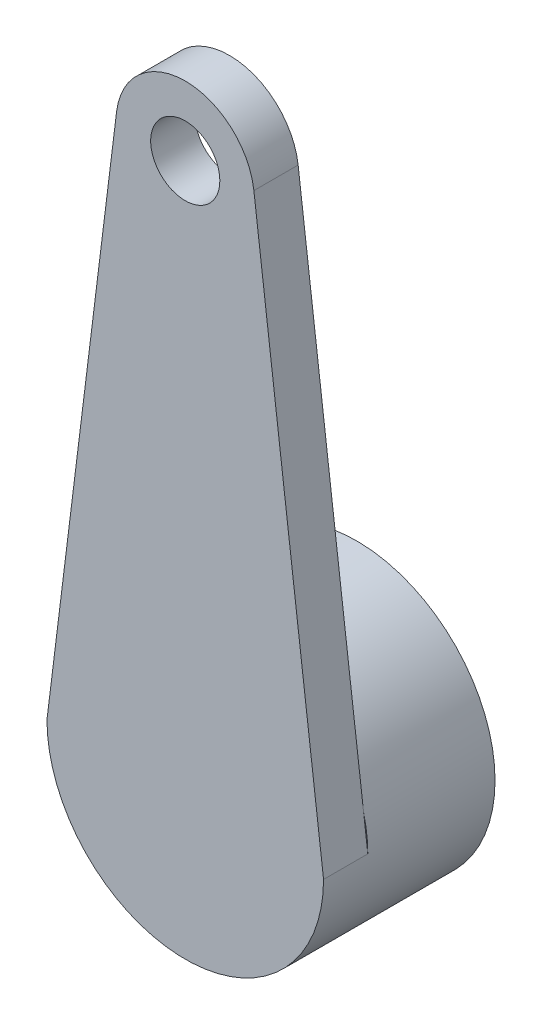
SolidWorks part; units mm, degrees
ref_plane "Front Plane" through (0, 0, 0) normal (0, 0, 1) x (1, 0, 0)
ref_plane "Top Plane" through (0, 0, 0) normal (0, 1, 0) x (1, 0, 0)
ref_plane "Right Plane" through (0, 0, 0) normal (1, 0, 0) x (0, 0, -1)
sketch "Sketch1" plane through (0, 0, 0) normal (0, 0, 1) x (1, 0, 0)
  circle A0 centre (6780.7758, 3542.5681) radius 4.064
  circle A1 centre (6780.7758, 3542.5681) radius 6.35
extrude "Boss-Extrude1" add sketch "Sketch1" along normal blind 5.842
sketch "Sketch2" plane through (0, 0, 5.842) normal (0, 0, 1) x (1, 0, 0)
  line L0 (6774.4258, 3542.5681) -> (6777.625, 3568.359)
  line L1 (6787.1258, 3542.5681) -> (6783.9267, 3568.359)
  arc A0 (6774.4258, 3542.5681) -> (6787.1258, 3542.5681) centre (6780.7758, 3542.5681) ccw
  circle A1 centre (6780.7758, 3567.9681) radius 1.5875
  arc A2 (6783.9267, 3568.359) -> (6777.625, 3568.359) centre (6780.7758, 3567.9681) ccw
extrude "Boss-Extrude2" add sketch "Sketch2" along normal blind 2.032
